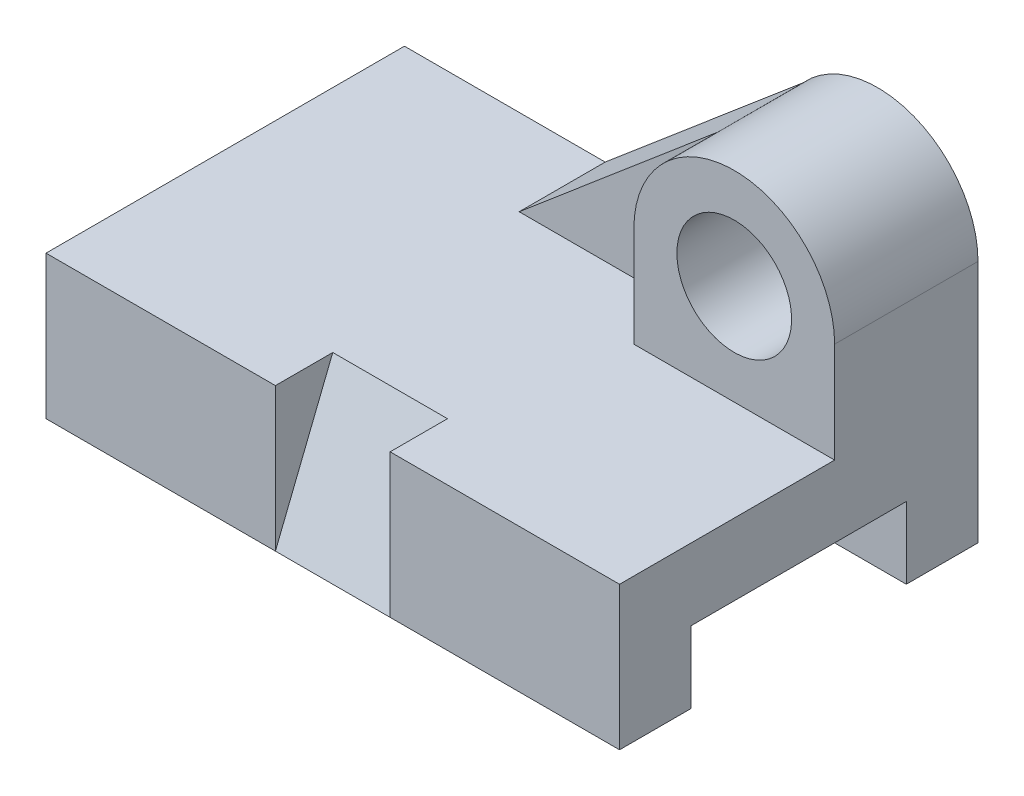
SolidWorks part; units mm, degrees
ref_plane "Front Plane" through (0, 0, 0) normal (0, 0, 1) x (1, 0, 0)
ref_plane "Top Plane" through (0, 0, 0) normal (0, 1, 0) x (1, 0, 0)
ref_plane "Right Plane" through (0, 0, 0) normal (1, 0, 0) x (0, 0, -1)
sketch "Sketch1" plane through (0, 0, 0) normal (0, 1, 0) x (1, 0, 0)
  line L1 (-100, -62.5) -> (100, -62.5)
  line L2 (-100, -62.5) -> (-100, 62.5)
  line L3 (-100, 62.5) -> (100, 62.5)
  line L4 (100, -62.5) -> (100, 62.5)
  line L5 (-100, -62.5) -> (100, 62.5) construction
  line L6 (-100, 62.5) -> (100, -62.5) construction
  point P0 (0, 0)
  dimension "D1" = 200
  dimension "D2" = 125
extrude "Boss-Extrude2" add sketch "Sketch1" along normal blind 50
sketch "Sketch3" plane through (0, 0, -62.5) normal (0, 0, -1) x (-1, 0, 0)
  line L0 (-100, 50) -> (-100, 85)
  line L1 (-30, 85) -> (-30, 50)
  line L2 (-100, 50) -> (100, 50) construction
  line L3 (-30, 50) -> (-100, 50)
  arc A0 (-100, 85) -> (-30, 85) centre (-65, 85) cw
  circle A1 centre (-65, 85) radius 20
  dimension "D1" = 35
  dimension "D3" = 40
  dimension "D2" = 35
extrude "Boss-Extrude5" add sketch "Sketch3" against normal blind 50
sketch "Sketch6" plane through (-100, 0, 0) normal (-1, 0, 0) x (0, 0, 1)
  line L0 (-62.5, 0) -> (62.5, 0) construction
  line L1 (-37.5, 0) -> (37.5, 0)
  line L2 (-37.5, 0) -> (-37.5, 25)
  line L3 (-37.5, 25) -> (37.5, 25)
  line L4 (37.5, 0) -> (37.5, 25)
  line L5 (-62.5, 50) -> (-62.5, 0) construction
  line L6 (62.5, 50) -> (62.5, 0) construction
  dimension "D1" = 25
  dimension "D2" = 25
  dimension "D3" = 25
extrude "Cut-Extrude1" cut sketch "Sketch6" against normal through all
sketch "Sketch7" plane through (0, 0, -62.5) normal (0, 0, -1) x (-1, 0, 0)
  line L0 (-39.1083, 108.5503) -> (30, 50)
  line L1 (-30, 50) -> (100, 50) construction
  line L2 (30, 50) -> (-30, 50)
  line L3 (-30, 50) -> (-30, 85)
  arc A0 (-30, 85) -> (-100, 85) centre (-65, 85) ccw construction
  arc A1 (-30, 85) -> (-39.1083, 108.5503) centre (-65, 85) ccw
  dimension "D1" = 70
extrude "Boss-Extrude6" add sketch "Sketch7" against normal blind 30
sketch "Sketch8" plane through (0, 0, 62.5) normal (0, 0, 1) x (1, 0, 0)
  line L0 (-20, 0) -> (-20, 50)
  line L1 (-100, 0) -> (100, 0) construction
  line L2 (30, 50) -> (-30, 50) construction
  line L3 (-20, 50) -> (20, 50)
  line L4 (-100, 50) -> (100, 50) construction
  line L5 (20, 50) -> (20, 0)
  line L6 (20, 0) -> (-20, 0)
  line L7 (-100, 50) -> (-100, 0) construction
  dimension "D1" = 40
  dimension "D2" = 80
extrude "Cut-Extrude2" cut sketch "Sketch8" against normal blind 20
sketch "Sketch9" plane through (20, 0, 0) normal (-1, 0, 0) x (0, 0, 1)
  line L0 (42.5, 50) -> (62.5, 0)
  line L1 (42.5, 50) -> (42.5, 0)
  line L2 (42.5, 0) -> (62.5, 0)
extrude "Boss-Extrude7" add sketch "Sketch9" along normal blind 40
